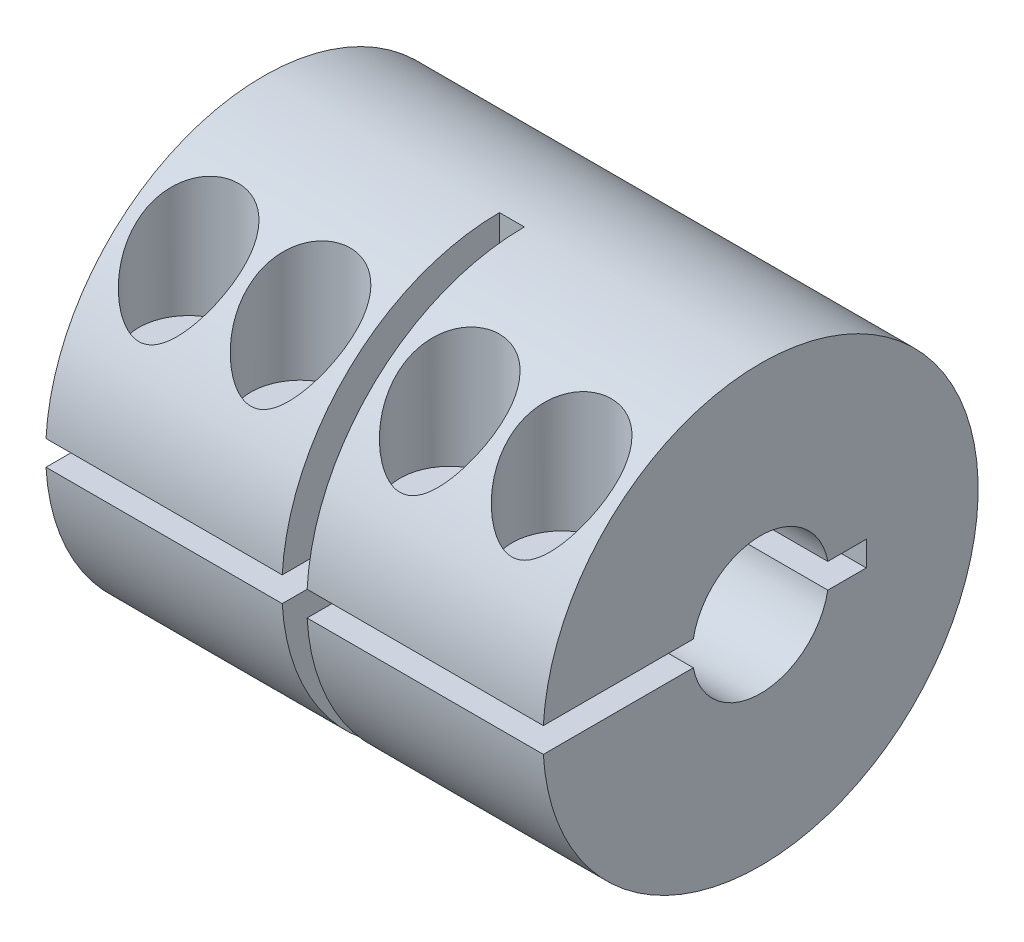
SolidWorks part; units mm, degrees
material "Сталь 45 ГОСТ 1050-88"
ref_plane "Front Plane" through (0, 0, 0) normal (0, 0, 1) x (1, 0, 0)
ref_plane "Top Plane" through (0, 0, 0) normal (0, 1, 0) x (1, 0, 0)
ref_plane "Right Plane" through (0, 0, 0) normal (1, 0, 0) x (0, 0, -1)
sketch "Skizze2" plane through (0, 0, 0) normal (0, 0, 1) x (1, 0, 0)
  line L0 (0, 0) -> (0, 17.5)
  line L2 (40, 17.5) -> (40, 0)
  line L3 (40, 0) -> (0, 0)
  line L4 (0, 17.5) -> (40, 17.5) construction
  line L5 (0, 17.5) -> (40, 17.5)
revolve "Rotation1" add sketch "Skizze2" angle 360 about L4
sketch "Skizze3" plane through (0, 0, 0) normal (-1, 0, 0) x (0, 0, 1)
  line L0 (5.4083, 18.5) -> (19.8262, 18.5)
  line L1 (19.8262, 18.5) -> (19.8262, 16.5)
  line L2 (-8.5, 17.5) -> (-8.5, 18.5)
  line L3 (-8.5, 18.5) -> (-5.4083, 18.5)
  line L4 (-8.5, 17.5) -> (-8.5, 16.5)
  line L5 (-8.5, 16.5) -> (-5.4083, 16.5)
  line L6 (19.8262, 16.5) -> (5.4083, 16.5)
  arc A0 (-5.4083, 16.5) -> (5.4083, 16.5) centre (0, 17.5) ccw
  arc A1 (5.4083, 18.5) -> (-5.4083, 18.5) centre (0, 17.5) ccw
extrude "Schnitt-Linear austragen1" cut sketch "Skizze3" against normal through all
sketch "Skizze5" plane through (0, 0, -8.5) normal (0, 0, 1) x (1, 0, 0)
  line L0 (40, 35) -> (0, 35) construction
  line L1 (40, 35) -> (0, 35)
  line L2 (0, 0) -> (40, 0) construction
  line L3 (0, 0) -> (40, 0)
  line L4 (0, 18.5) -> (0, 16.5)
  line L5 (0, 16.5) -> (40, 16.5)
  line L6 (40, 16.5) -> (40, 18.5)
  line L7 (40, 18.5) -> (0, 18.5)
  line L8 (0, 18.5) -> (0, 16.5)
  line L9 (0, 16.5) -> (40, 16.5)
  line L10 (40, 16.5) -> (40, 18.5)
  line L11 (40, 18.5) -> (0, 18.5)
  dimension "D1" = 0
sketch "Skizze6" plane through (0, 0, 0) normal (0, 0, 1) x (1, 0, 0)
  line L0 (0, 0) -> (40, 0) construction
  line L1 (19, 0) -> (21, 0)
  line L2 (40, 35) -> (0, 35) construction
  line L3 (21, 35) -> (19, 35)
  line L4 (21, 16.5) -> (21, 0)
  line L6 (0, 18.5) -> (0, 16.5)
  line L7 (0, 16.5) -> (40, 16.5)
  line L8 (40, 16.5) -> (40, 18.5)
  line L9 (40, 18.5) -> (0, 18.5)
  line L11 (19, 16.5) -> (21, 16.5)
  line L13 (21, 18.5) -> (19, 18.5)
  line L14 (19, 16.5) -> (19, 0)
  line L15 (21, 18.5) -> (21, 35)
  line L17 (19, 18.5) -> (19, 35)
  dimension "D1" = 0
extrude "Schnitt-Linear austragen3" cut sketch "Skizze6" along normal through all
sketch "Skizze7" plane through (0, 0, 0) normal (0, 1, 0) x (1, 0, 0)
  line L2 (40, -17.4714) -> (40, 17.5) construction
  line L3 (40, -17.4714) -> (40, 17.5)
  line L4 (0, 17.5) -> (0, -17.4714) construction
  line L5 (0, 17.5) -> (0, -17.4714)
  line L6 (19, -17.4714) -> (19, 0) construction
  line L7 (21, 0) -> (21, -17.4714) construction
  line L8 (19, -17.4714) -> (19, 0)
  line L9 (21, 0) -> (21, -17.4714)
  line L10 (21, -11) -> (40, -11)
  line L11 (19, -11) -> (0, -11)
ref_plane "Ebene1" through (0, 35, 0) normal (0, 1, 0) x (1, 0, 0)
sketch "Skizze10" plane through (0, 35, 0) normal (0, 1, 0) x (1, 0, 0)
  line L0 (0, 17.5) -> (0, -17.4714) construction
  line L1 (0, 0) -> (0, -17.4714)
  line L2 (0, -17.4714) -> (19, -17.4714) construction
  line L3 (0, -17.4714) -> (19, -17.4714)
  line L4 (40, -17.4714) -> (40, 17.5) construction
  line L5 (40, -17.4714) -> (40, 0)
  line L6 (21, 0) -> (19, 0) construction
  line L7 (40, 0) -> (0, 0)
  line L8 (21, -5.4083) -> (21, -17.4714)
  line L9 (21, -17.4714) -> (40, -17.4714)
  line L10 (40, -17.4714) -> (40, -5.4083)
  line L11 (40, -5.4083) -> (21, -5.4083)
  line L13 (21, -17.4714) -> (40, -17.4714)
  line L16 (19, -17.4714) -> (19, 0) construction
  line L17 (0, -11) -> (19, -11)
  line L18 (19, -17.4714) -> (19, 0)
  line L19 (21, 0) -> (21, -17.4714) construction
  line L20 (21, 0) -> (21, -17.4714)
  line L21 (21, -11) -> (40, -11)
  line L22 (30, -11) -> (31, -11)
  line L23 (21, -11) -> (26, -11)
  line L24 (31, -11) -> (35, -11)
  line L25 (0, -11) -> (1, -11)
  line L26 (1, -11) -> (5, -11)
  line L27 (9, -11) -> (10.4564, -11)
  line L28 (9, -11) -> (10, -11)
  line L29 (10, -11) -> (14, -11)
  circle A0 centre (26, -11) radius 4
  circle A1 centre (35, -11) radius 4
  circle A2 centre (5, -11) radius 4
  circle A3 centre (14, -11) radius 4
  dimension "D1" = 0
extrude "Schnitt-Linear austragen4" cut sketch "Skizze10" against normal blind 11.5 contours A2 | A3 | A0 | A1
sketch "Skizze11" plane through (0, 23.5, 0) normal (0, 1, 0) x (1, 0, 0)
  point P0 (5, -11)
  point P2 (35, -11)
  point P4 (26, -11)
  point P6 (14, -11)
hole_wizard "Kernloch für M4 Gewinde1" positions "3D-Skizze1" profile "Skizze12" hole size "M4" standard "DIN" end condition through all
sketch3d "3D-Skizze1"
  point P0 (5, 23.5, 11)
  point P3 (14, 23.5, 11)
  point P6 (26, 23.5, 11)
  point P9 (35, 23.5, 11)
sketch "Skizze12" plane through (5, 23.5, 11) normal (1, 0, 0) x (0, 0, 1)
  line L0 (0, 0) -> (0, 23.5)
  line L1 (0, 23.5) -> (1.65, 23.5)
  line L2 (1.65, 23.5) -> (1.65, 0)
  line L5 (1.65, 0) -> (0, 0)
  line L11 (0, -6.35) -> (0, 107.95) construction
  dimension "Bohrerdurchmesser" = 3.3
  dimension "Bohrungstiefe" = 23.5
